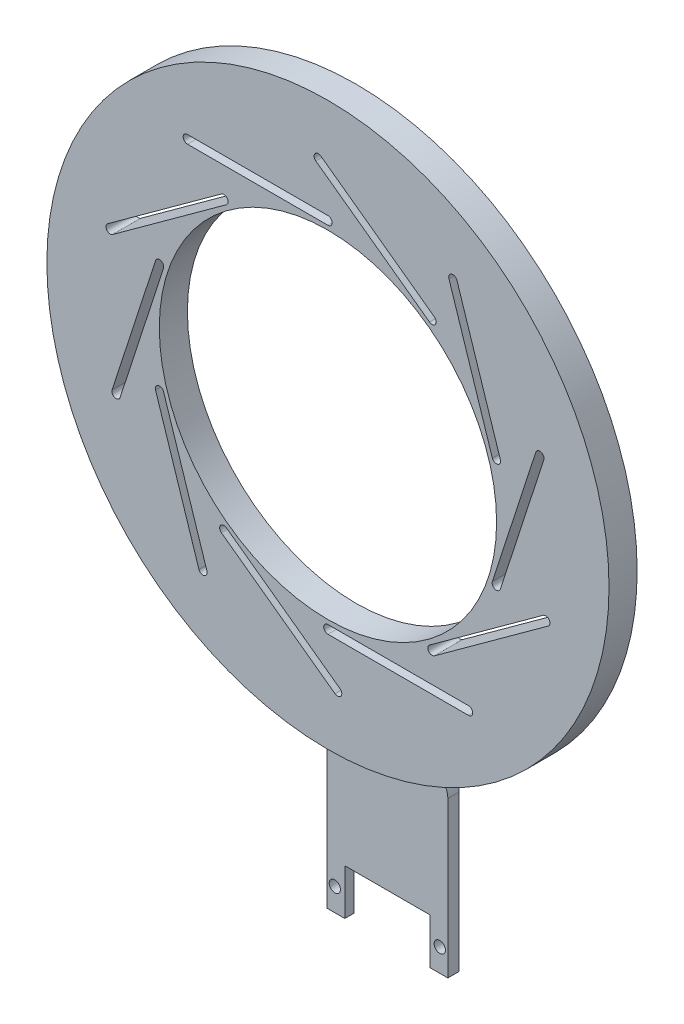
SolidWorks part; units mm, degrees
ref_plane "Front" through (0, 0, 0) normal (0, 0, 1) x (1, 0, 0)
ref_plane "Top" through (0, 0, 0) normal (0, 1, 0) x (1, 0, 0)
ref_plane "Right" through (0, 0, 0) normal (1, 0, 0) x (0, 0, -1)
sketch "Sketch1" plane through (0, 0, 0) normal (0, 0, 1) x (1, 0, 0)
  line L0 (0, 0) -> (0, 1000) construction
  line L3 (0, 630) -> (-500, 630) construction
  line L4 (0, 615) -> (-500, 615)
  line L5 (0, 645) -> (-500, 645)
  line L12 (370.3047, 509.6807) -> (-34.2038, 803.5733) construction
  line L18 (361.4879, 497.5455) -> (-43.0206, 791.4381)
  line L24 (379.1215, 521.816) -> (-25.387, 815.7086)
  line L30 (598.8566, 195.6318) -> (599.1656, 194.6807) construction
  line L35 (599.1656, 194.6807) -> (444.6571, 670.209) construction
  line L36 (584.8998, 190.0455) -> (430.3913, 665.5737)
  line L41 (613.4315, 199.316) -> (458.923, 674.8442)
  line L42 (599.4746, -193.7296) -> (599.1656, -194.6807) construction
  line L47 (599.1656, -194.6807) -> (753.6741, 280.8476) construction
  line L48 (584.8998, -190.0455) -> (739.4083, 285.4828)
  line L53 (613.4315, -199.316) -> (767.94, 276.2123)
  line L54 (371.1137, -509.0929) -> (370.3047, -509.6807) construction
  line L56 (370.3047, -509.6807) -> (774.8132, -215.7881) construction
  line L57 (361.4879, -497.5455) -> (765.9964, -203.6528)
  line L58 (379.1215, -521.816) -> (783.63, -227.9233)
  line L59 (1, -630) -> (0, -630) construction
  line L60 (0, -630) -> (500, -630) construction
  line L61 (0, -615) -> (500, -615)
  line L62 (0, -645) -> (500, -645)
  line L63 (-369.4957, -510.2685) -> (-370.3047, -509.6807) construction
  line L64 (-370.3047, -509.6807) -> (34.2038, -803.5733) construction
  line L65 (-361.4879, -497.5455) -> (43.0206, -791.4381)
  line L66 (-379.1215, -521.816) -> (25.387, -815.7086)
  line L67 (-598.8566, -195.6318) -> (-599.1656, -194.6807) construction
  line L68 (-599.1656, -194.6807) -> (-444.6571, -670.209) construction
  line L69 (-584.8998, -190.0455) -> (-430.3913, -665.5737)
  line L70 (-613.4315, -199.316) -> (-458.923, -674.8442)
  line L71 (-599.4746, 193.7296) -> (-599.1656, 194.6807) construction
  line L72 (-599.1656, 194.6807) -> (-753.6741, -280.8476) construction
  line L73 (-584.8998, 190.0455) -> (-739.4083, -285.4828)
  line L74 (-613.4315, 199.316) -> (-767.94, -276.2123)
  line L75 (-371.1137, 509.0929) -> (-370.3047, 509.6807) construction
  line L76 (-370.3047, 509.6807) -> (-774.8132, 215.7881) construction
  line L77 (-361.4879, 497.5455) -> (-765.9964, 203.6528)
  line L78 (-379.1215, 521.816) -> (-783.63, 227.9233)
  line L79 (0, 0) -> (587.7853, 809.017) construction
  circle A0 centre (0, 0) radius 600
  circle A1 centre (0, 0) radius 1000
  circle A4 centre (0, 0) radius 630 construction
  arc A5 (0, 615) -> (0, 645) centre (0, 630) ccw
  arc A6 (-500, 645) -> (-500, 615) centre (-500, 630) ccw
  arc A25 (361.4879, 497.5455) -> (379.1215, 521.816) centre (370.3047, 509.6807) ccw
  arc A26 (-25.387, 815.7086) -> (-43.0206, 791.4381) centre (-34.2038, 803.5733) ccw
  arc A27 (584.8998, 190.0455) -> (613.4315, 199.316) centre (599.1656, 194.6807) ccw
  arc A28 (458.923, 674.8442) -> (430.3913, 665.5737) centre (444.6571, 670.209) ccw
  arc A29 (584.8998, -190.0455) -> (613.4315, -199.316) centre (599.1656, -194.6807) ccw
  arc A30 (767.94, 276.2123) -> (739.4083, 285.4828) centre (753.6741, 280.8476) ccw
  arc A31 (361.4879, -497.5455) -> (379.1215, -521.816) centre (370.3047, -509.6807) ccw
  arc A32 (783.63, -227.9233) -> (765.9964, -203.6528) centre (774.8132, -215.7881) ccw
  arc A33 (0, -615) -> (0, -645) centre (0, -630) ccw
  arc A34 (500, -645) -> (500, -615) centre (500, -630) ccw
  arc A35 (-361.4879, -497.5455) -> (-379.1215, -521.816) centre (-370.3047, -509.6807) ccw
  arc A36 (25.387, -815.7086) -> (43.0206, -791.4381) centre (34.2038, -803.5733) ccw
  arc A37 (-584.8998, -190.0455) -> (-613.4315, -199.316) centre (-599.1656, -194.6807) ccw
  arc A38 (-458.923, -674.8442) -> (-430.3913, -665.5737) centre (-444.6571, -670.209) ccw
  arc A39 (-584.8998, 190.0455) -> (-613.4315, 199.316) centre (-599.1656, 194.6807) ccw
  arc A40 (-767.94, -276.2123) -> (-739.4083, -285.4828) centre (-753.6741, -280.8476) ccw
  arc A41 (-361.4879, 497.5455) -> (-379.1215, 521.816) centre (-370.3047, 509.6807) ccw
  arc A42 (-783.63, 227.9233) -> (-765.9964, 203.6528) centre (-774.8132, 215.7881) ccw
  point P8 (-250, 630)
  point P19 (168.0505, 656.627)
  point P27 (521.9114, 432.4448)
  point P35 (676.4199, 43.0834)
  point P43 (572.559, -362.7344)
  point P51 (250, -630)
  point P59 (-168.0505, -656.627)
  point P67 (-521.9114, -432.4448)
  point P75 (-676.4199, -43.0834)
  point P83 (-572.559, 362.7344)
  point P89 (0, 0)
  dimension "D1" = 2000
  dimension "D2" = 500
  dimension "D3" = 630
  dimension "D4" = 15
  dimension "D6" = 10
extrude "Boss-Extrude1" add sketch "Sketch1" along normal blind 100
scale "Echelle1" bodies to scale 101 scale about centroid uniform scaling yes scale factor 0.075
sketch "Esquisse1" plane through (0, 0, 46.25) normal (0, 0, -1) x (-1, 0, 0)
  line L0 (0.012, -104.1149) -> (0.012, -116.3149)
  line L1 (-27.488, -116.3149) -> (-22.688, -116.3149)
  line L2 (-27.488, -116.3149) -> (-27.488, -74.8455)
  line L4 (4.812, -116.3149) -> (4.812, -74.8455)
  line L5 (-22.688, -104.1149) -> (-22.688, -116.3149)
  line L6 (0.012, -104.1149) -> (-22.688, -104.1149)
  line L7 (0.012, -116.3149) -> (4.812, -116.3149)
  circle A0 centre (0, 0) radius 75 construction
  arc A1 (-27.488, -74.8455) -> (-25.2574, -70.6191) centre (-22.3688, -74.8455) cw
  arc A2 (-25.2574, -70.6191) -> (4.812, -74.8455) centre (0, 0) ccw
  circle A3 centre (-25.338, -110.2149) radius 1.5
  circle A4 centre (2.662, -110.2149) radius 1.5
extrude "Boss.-Extru.1" add sketch "Esquisse1" against normal blind 3
fillet "Congé1" radius 1 1 edges at (25.2574, -70.6191, 47.75)
fillet "Congé3" radius 1 1 edges at (-4.812, -74.8455, 47.75)
chamfer "Chanfrein1" distance 0.5 angle 45 3 edges at (-0.012, -110.2149, 46.25) (11.338, -104.1149, 46.25) (22.688, -110.2149, 46.25)
